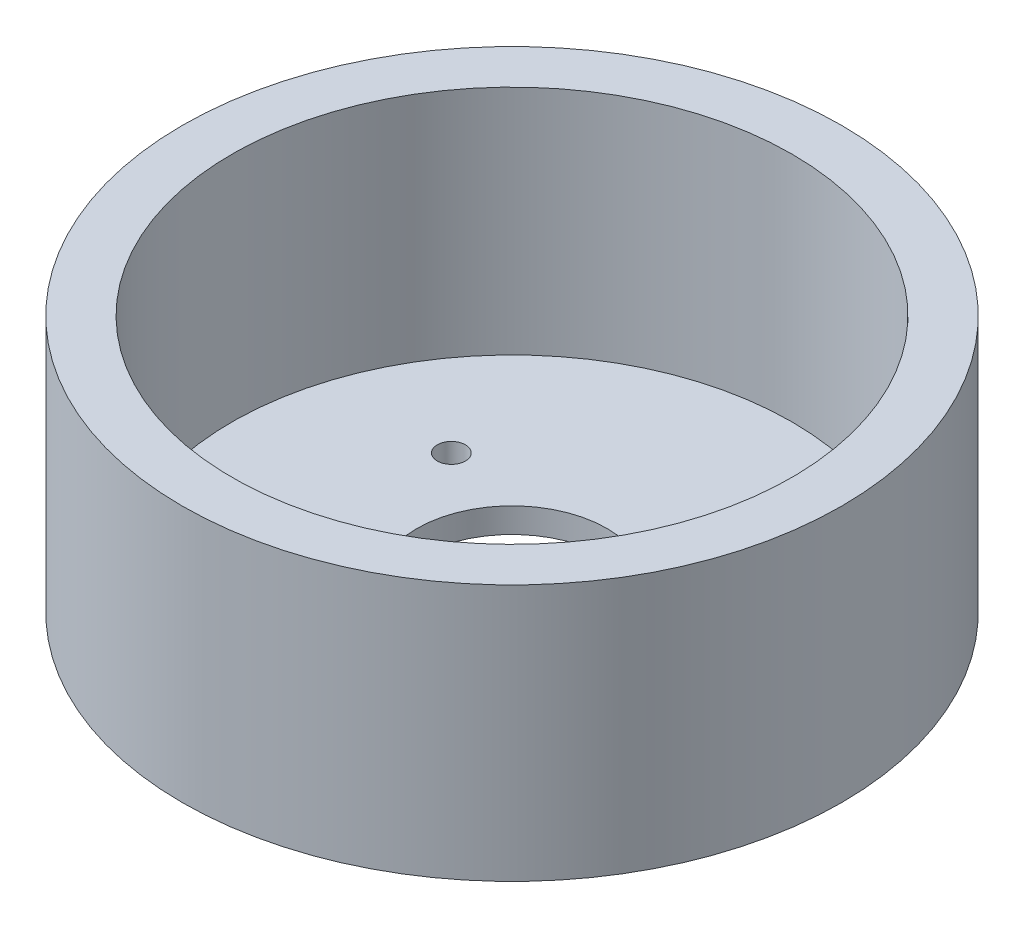
SolidWorks part; units mm, degrees
material "PLA"
ref_plane "前视基准面" through (0, 0, 0) normal (0, 0, 1) x (1, 0, 0)
ref_plane "上视基准面" through (0, 0, 0) normal (0, 1, 0) x (1, 0, 0)
ref_plane "右视基准面" through (0, 0, 0) normal (1, 0, 0) x (0, 0, -1)
sketch "草图1" plane through (0, 0, 0) normal (0, 0, 1) x (1, 0, 0)
  line L0 (0, 0) -> (0, 26.5738) construction
  line L1 (39.8, 31) -> (39.8, 0)
  line L2 (39.8, 0) -> (0, 0)
  line L3 (0, 0) -> (0, 3)
  line L4 (0, 3) -> (33.8, 3)
  line L5 (33.8, 3) -> (33.8, 31)
  line L6 (33.8, 31) -> (39.8, 31)
  dimension "D1" = 33.8
  dimension "D2" = 3
  dimension "D3" = 6
  dimension "D4" = 28
revolve "旋转1" add sketch "草图1" angle 360 about L0
sketch "草图2" plane through (0, 0, 0) normal (0, -1, 0) x (1, 0, 0)
  circle A0 centre (0, 0) radius 11.5
  circle A1 centre (0, 0) radius 20 construction
  circle A2 centre (0, 20) radius 1.7
  circle A3 centre (17.3205, -10) radius 1.7
  circle A4 centre (-17.3205, -10) radius 1.7
  point P13 (0, 0)
  dimension "D1" = 23
  dimension "D2" = 40
  dimension "D3" = 3.4
  dimension "D4" = 3
extrude "切除-拉伸1" cut sketch "草图2" against normal through all
